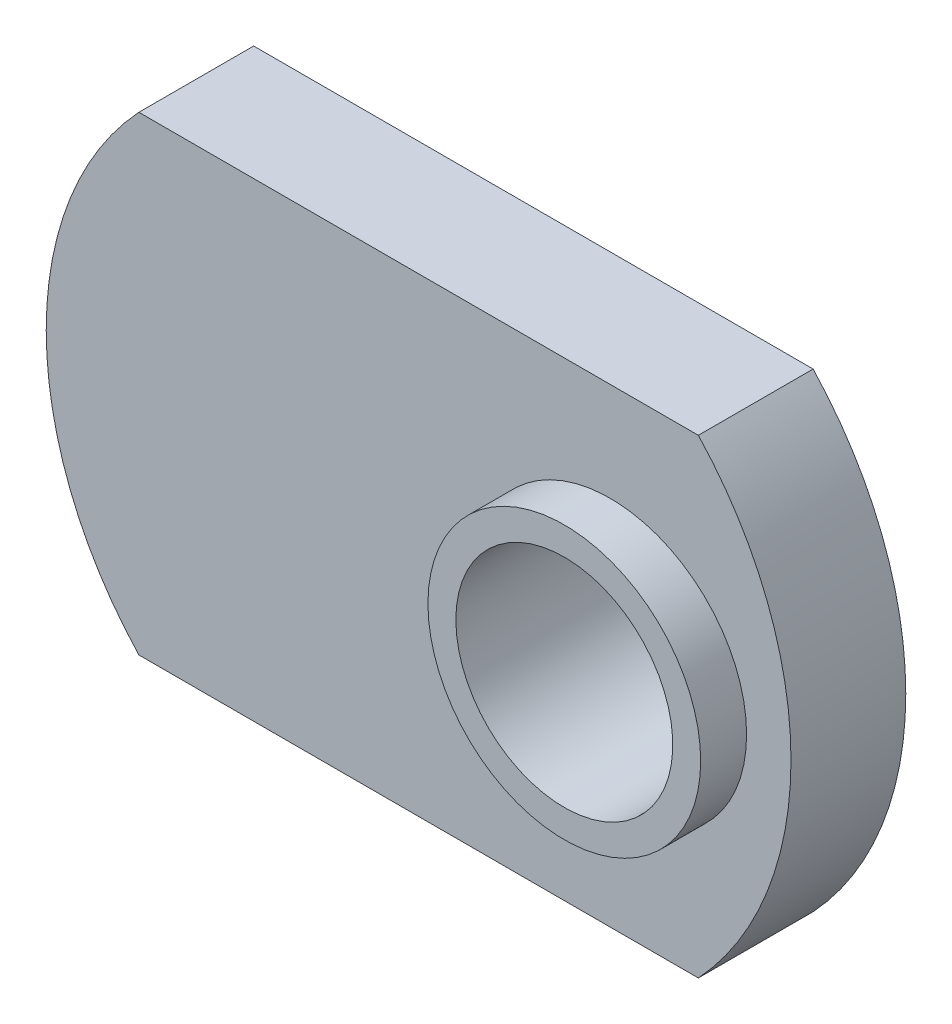
SolidWorks part; units mm, degrees
material "Chrome Stainless Steel"
ref_plane "Front Plane" through (0, 0, 0) normal (0, 0, 1) x (1, 0, 0)
ref_plane "Top Plane" through (0, 0, 0) normal (0, 1, 0) x (1, 0, 0)
ref_plane "Right Plane" through (0, 0, 0) normal (1, 0, 0) x (0, 0, -1)
sketch "Sketch1" plane through (0, 0, 0) normal (0, 0, 1) x (1, 0, 0)
  line L0 (101.7537, 126.7205) -> (122.3537, 126.7205) construction
  line L1 (104.3162, 133.2205) -> (119.7911, 133.2205)
  line L2 (104.3162, 120.2205) -> (119.7911, 120.2205)
  arc A0 (104.3162, 120.2205) -> (104.3162, 133.2205) centre (111.2787, 126.7205) cw
  arc A1 (119.7911, 120.2205) -> (119.7911, 133.2205) centre (112.8287, 126.7205) ccw
  dimension "D1" = 9.525
  dimension "D3" = 20.6
  dimension "D2" = 9.525
  dimension "D4" = 13
extrude "Extrude1" add sketch "Sketch1" along normal blind 3.175
sketch "Sketch4" plane through (0, 0, 3.175) normal (0, 0, 1) x (1, 0, 0)
  line L1 (101.7537, 126.7205) -> (122.3537, 126.7205) construction
  arc A1 (104.3162, 133.2205) -> (104.3162, 120.2205) centre (111.2787, 126.7205) ccw construction
  arc A2 (119.7911, 120.2205) -> (119.7911, 133.2205) centre (112.8287, 126.7205) ccw construction
  circle A3 centre (117.3537, 126.7205) radius 3.772
  dimension "D2" = 5
extrude "Extrude3" add sketch "Sketch4" along normal blind 1.27
sketch "Sketch6" plane through (0, 0, 0) normal (0, 0, -1) x (-1, 0, 0)
  circle A1 centre (-117.3537, 126.7205) radius 3
extrude "Cut-Extrude1" cut sketch "Sketch6" against normal through all
